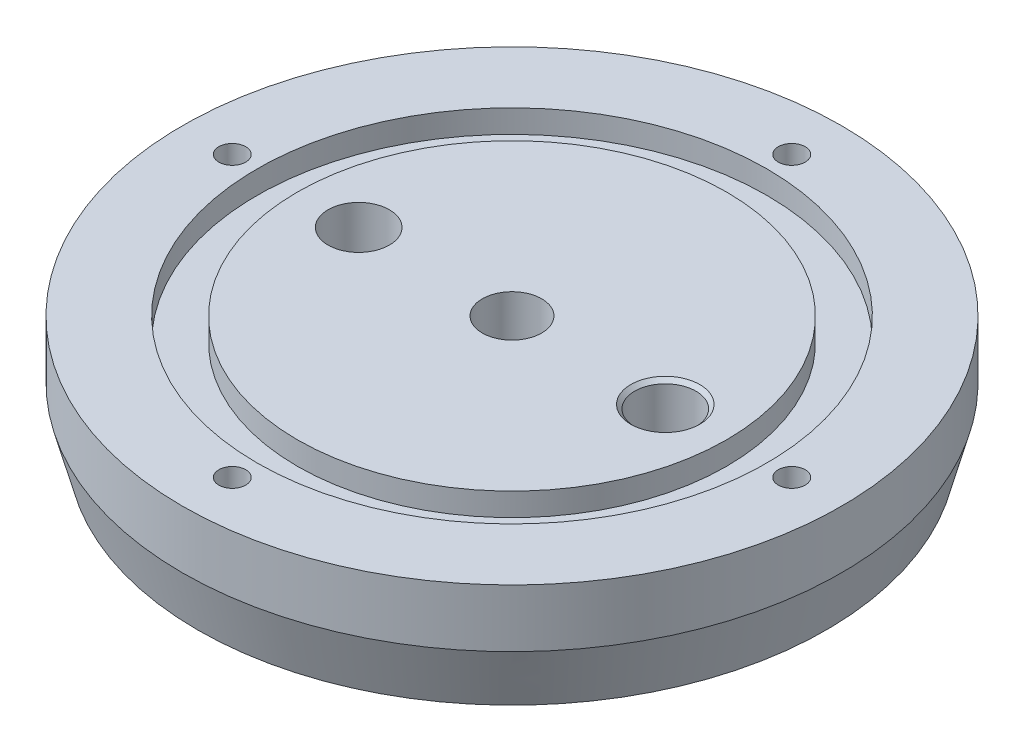
SolidWorks part; units mm, degrees
ref_plane "Front Plane" through (0, 0, 0) normal (0, 0, 1) x (1, 0, 0)
ref_plane "Top Plane" through (0, 0, 0) normal (0, 1, 0) x (1, 0, 0)
ref_plane "Right Plane" through (0, 0, 0) normal (1, 0, 0) x (0, 0, -1)
sketch "Sketch1" plane through (0, 0, 0) normal (0, 1, 0) x (1, 0, 0)
  circle A0 centre (0, 0) radius 43
  dimension "D1" = 86
extrude "Boss-Extrude1" add sketch "Sketch1" along normal blind 15
sketch "Sketch2" plane through (0, 0, 0) normal (0, -1, 0) x (1, 0, 0)
  circle A0 centre (20, 0) radius 4
  circle A1 centre (-20, 0) radius 4
  dimension "D1" = 8
  dimension "D2" = 8
  dimension "D3" = 20
  dimension "D4" = 20
extrude "Cut-Extrude1" cut sketch "Sketch2" against normal through all
sketch "Sketch3" plane through (0, 15, 0) normal (0, 1, 0) x (1, 0, 0)
  circle A0 centre (0, 0) radius 3.875
  dimension "D1" = 7.75
extrude "Cut-Extrude2" cut sketch "Sketch3" against normal through all
sketch "Sketch4" plane through (0, 15, 0) normal (0, 1, 0) x (1, 0, 0)
  circle A0 centre (0, 0) radius 28
  circle A1 centre (0, 0) radius 33.25
  dimension "D1" = 56
  dimension "D2" = 66.5
extrude "Cut-Extrude3" cut sketch "Sketch4" against normal blind 3
sketch "Sketch5" plane through (0, 0, 0) normal (0, -1, 0) x (1, 0, 0)
  circle A0 centre (36.5, 0) radius 1.75
  dimension "D1" = 36.5
  dimension "D2" = 3.5
extrude "Cut-Extrude4" cut sketch "Sketch5" against normal through all
pattern_circular "CirPattern1" count 4 over 360 about axis through (0, 0, 0) along (0, 1, 0) of "Cut-Extrude4"
chamfer "Chamfer1" distance 2 angle 75 1 edges at (0, 0, 43)
chamfer "Chamfer2" distance 0.5 angle 45 4 edges at (20, 0, -4) (20, 15, -4) (0, 0, 3.875) (-20, 0, -4)
